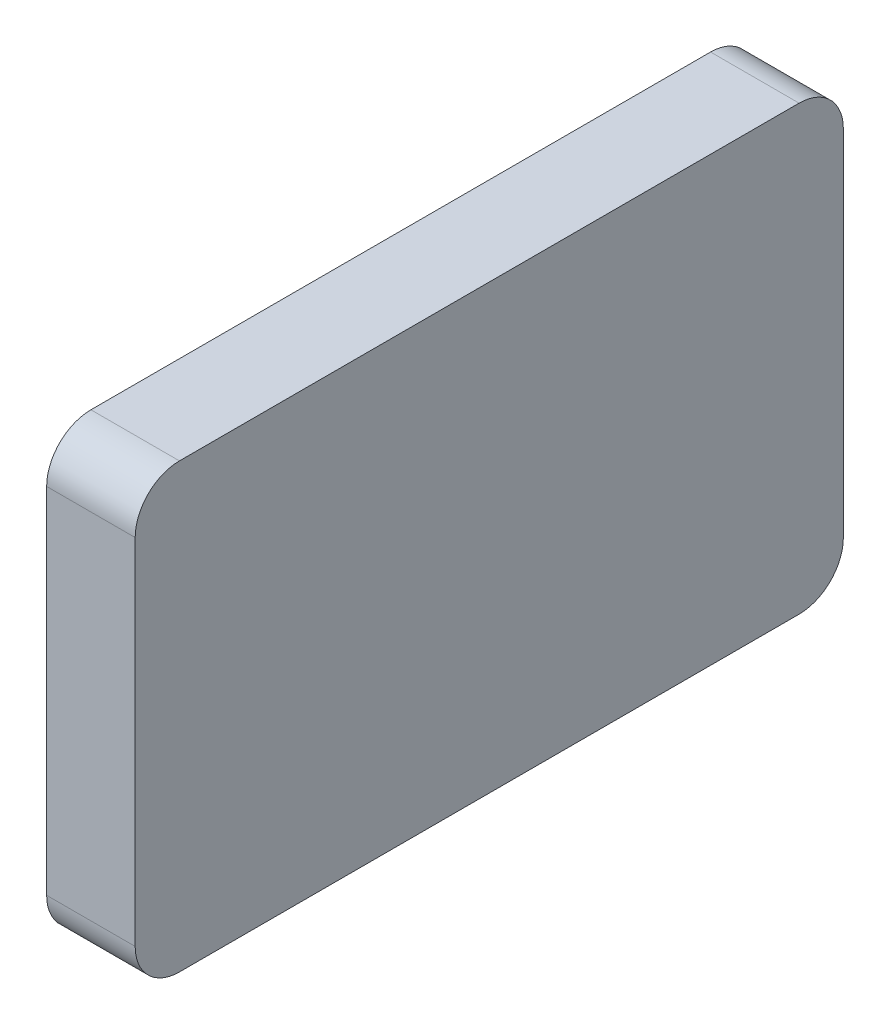
SolidWorks part; units mm, degrees
material "Chrome Stainless Steel"
ref_plane "Front Plane" through (0, 0, 0) normal (0, 0, 1) x (1, 0, 0)
ref_plane "Top Plane" through (0, 0, 0) normal (0, 1, 0) x (1, 0, 0)
ref_plane "Right Plane" through (0, 0, 0) normal (1, 0, 0) x (0, 0, -1)
sketch "BaseS" plane through (0, 0, 0) normal (1, 0, 0) x (0, 0, -1)
  line L1 (-4, 2.5) -> (4, 2.5)
  line L2 (-4, 2.5) -> (-4, -2.5)
  line L3 (-4, -2.5) -> (4, -2.5)
  line L4 (4, 2.5) -> (4, -2.5)
  line L5 (-4, 2.5) -> (4, -2.5) construction
  line L6 (-4, -2.5) -> (4, 2.5) construction
  point P0 (0, 0)
  dimension "Length" = 8
  dimension "Width" = 5
extrude "Base" add sketch "BaseS" along normal mid plane 1
fillet "BaseF" radius 0.5 4 edges at (0, -2.5, -4) (0, -2.5, 4) (0, 2.5, 4) (0, 2.5, -4)
